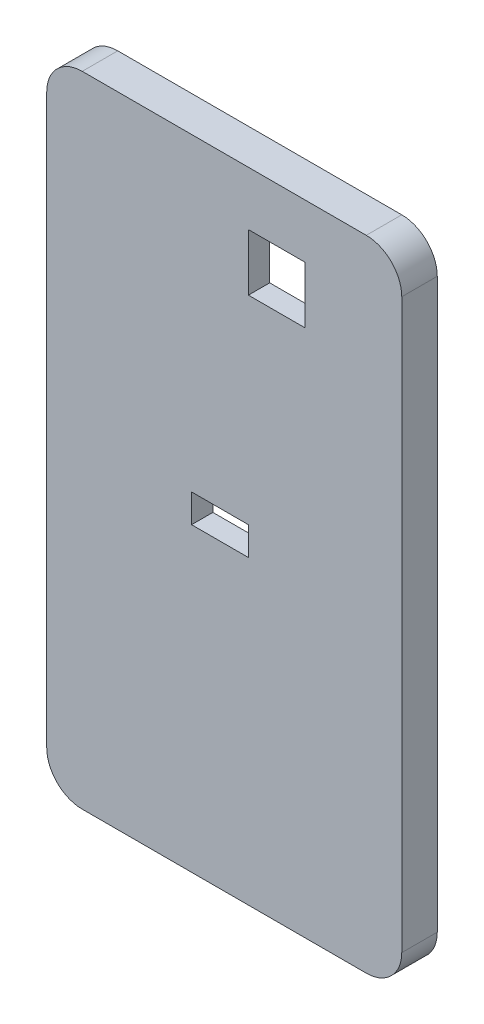
SolidWorks part; units mm, degrees
ref_plane "Front Plane" through (0, 0, 0) normal (0, 0, 1) x (1, 0, 0)
ref_plane "Top Plane" through (0, 0, 0) normal (0, 1, 0) x (1, 0, 0)
ref_plane "Right Plane" through (0, 0, 0) normal (1, 0, 0) x (0, 0, -1)
sketch "Sketch2" plane through (0, 0, 0) normal (0, 0, 1) x (1, 0, 0)
  line L1 (0, 0) -> (63.5, 0)
  line L2 (0, 0) -> (0, -114.3)
  line L3 (0, -114.3) -> (63.5, -114.3)
  line L4 (63.5, 0) -> (63.5, -114.3)
  dimension "D1" = 63.5
  dimension "D2" = 114.3
extrude "Boss-Extrude1" add sketch "Sketch2" along normal blind 6.35
fillet "Fillet1" radius 6.35 4 edges at (63.5, 0, 3.175) (63.5, -114.3, 3.175) (0, 0, 3.175) (0, -114.3, 3.175)
sketch "Sketch5" plane through (0, 0, 0) normal (0, 0, -1) x (-1, 0, 0)
  line L0 (-60.96, -6.4537) -> (-60.96, -107.95)
  line L1 (-63.5, -107.95) -> (-63.5, -6.35) construction
  line L2 (-57.15, -2.54) -> (-6.35, -2.54)
  line L3 (-57.15, 0) -> (-6.35, 0) construction
  line L4 (-2.54, -6.35) -> (-2.54, -107.95)
  line L5 (0, -6.35) -> (0, -107.95) construction
  line L6 (-6.35, -111.76) -> (-57.15, -111.76)
  line L7 (-6.35, -114.3) -> (-57.15, -114.3) construction
  arc A0 (-60.96, -6.4537) -> (-57.15, -2.54) centre (-57.1514, -6.35) cw
  arc A1 (-6.35, -2.54) -> (-2.54, -6.35) centre (-6.35, -6.35) cw
  arc A2 (-2.54, -107.95) -> (-6.35, -111.76) centre (-6.35, -107.95) cw
  arc A3 (-57.15, -111.76) -> (-60.96, -107.95) centre (-57.15, -107.95) cw
  dimension "D5" = 3.81
  dimension "D6" = 3.81
  dimension "D7" = 3.81
  dimension "D8" = 3.81
  dimension "D1" = 2.54
  dimension "D2" = 2.54
  dimension "D3" = 2.54
  dimension "D4" = 2.54
extrude "Cut-Extrude2" cut sketch "Sketch5" against normal blind 2.54
sketch "Sketch7" plane through (0, 0, 2.54) normal (0, 0, -1) x (-1, 0, 0)
  line L0 (-60.96, -6.4537) -> (-60.96, -107.95) construction
  line L1 (-50.038, -5.842) -> (-13.462, -5.842)
  line L2 (-50.038, -5.842) -> (-50.038, -73.152)
  line L3 (-50.038, -73.152) -> (-13.462, -73.152)
  line L4 (-13.462, -5.842) -> (-13.462, -73.152)
  line L5 (-2.54, -107.95) -> (-2.54, -6.35) construction
  line L6 (-6.35, -2.54) -> (-57.15, -2.54) construction
  line L7 (-57.15, -111.76) -> (-6.35, -111.76) construction
  line L9 (-36.068, -60.452) -> (-25.908, -60.452)
  line L10 (-36.068, -60.452) -> (-36.068, -55.372)
  line L11 (-36.068, -55.372) -> (-25.908, -55.372)
  line L12 (-25.908, -60.452) -> (-25.908, -55.372)
  dimension "D1" = 10.922
  dimension "D2" = 10.922
  dimension "D3" = 3.302
  dimension "D4" = 38.608
  dimension "D5" = 13.97
  dimension "D6" = 10.16
  dimension "D7" = 12.7
  dimension "D8" = 5.08
sketch "Sketch8" plane through (0, 0, 2.54) normal (0, 0, -1) x (-1, 0, 0)
  line L0 (-50.038, -5.842) -> (-13.462, -5.842) construction
  line L1 (-46.228, -9.652) -> (-36.068, -9.652)
  line L2 (-46.228, -9.652) -> (-46.228, -19.812)
  line L3 (-46.228, -19.812) -> (-36.068, -19.812)
  line L4 (-36.068, -9.652) -> (-36.068, -19.812)
  line L5 (-50.038, -5.842) -> (-50.038, -73.152) construction
  dimension "D1" = 3.81
  dimension "D2" = 3.81
  dimension "D3" = 10.16
  dimension "D4" = 10.16
extrude "Cut-Extrude3" cut sketch "Sketch8" against normal through all
extrude "Cut-Extrude4" cut sketch "Sketch7" against normal through all contours L9 L12 L11 L10
